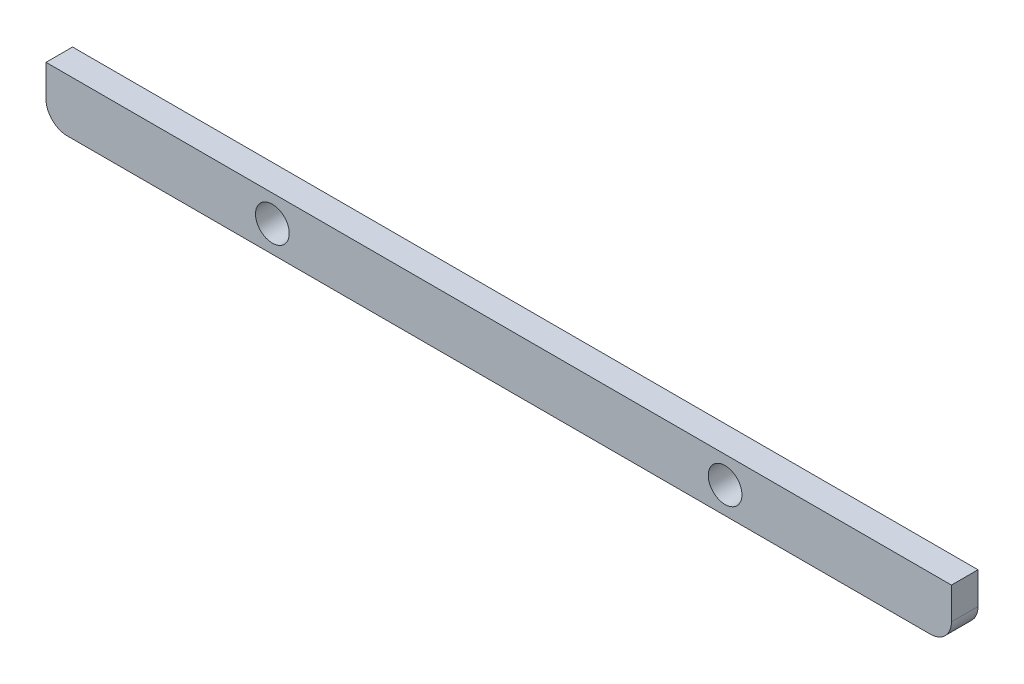
SolidWorks part; units mm, degrees
ref_plane "Alzado" through (0, 0, 0) normal (0, 0, 1) x (1, 0, 0)
ref_plane "Planta" through (0, 0, 0) normal (0, 1, 0) x (1, 0, 0)
ref_plane "Vista lateral" through (0, 0, 0) normal (1, 0, 0) x (0, 0, -1)
sketch "Croquis1" plane through (0, 0, 0) normal (0, 0, 1) x (1, 0, 0)
  line L1 (-85.24, 5) -> (85.24, 5)
  line L2 (-85.24, 5) -> (-85.24, -1)
  line L3 (-81.24, -5) -> (81.24, -5)
  line L4 (85.24, 5) -> (85.24, -1)
  line L5 (-85.24, 5) -> (85.24, -5) construction
  line L6 (-85.24, -5) -> (85.24, 5) construction
  arc A0 (81.24, -5) -> (85.24, -1) centre (81.24, -1) ccw
  arc A1 (-85.24, -1) -> (-81.24, -5) centre (-81.24, -1) ccw
  point P0 (0, 0)
  dimension "D3" = 4
  dimension "D1" = 170.48
  dimension "D2" = 10
extrude "Saliente-Extruir1" add sketch "Croquis1" along normal mid plane 5
sketch "Croquis2" plane through (0, 0, 2.5) normal (0, 0, 1) x (1, 0, 0)
  line L0 (-42.62, 0) -> (-85.24, 0) construction
  line L3 (-85.24, 5) -> (-85.24, -1) construction
  line L4 (-42.62, 0) -> (0, 0) construction
  line L5 (0, 0) -> (42.62, 0) construction
  line L6 (42.62, 0) -> (85.24, 0) construction
  line L7 (85.24, -1) -> (85.24, 5) construction
  circle A0 centre (42.62, 0) radius 3.175
  circle A1 centre (-42.62, 0) radius 3.175
  point P4 (0, 0)
  dimension "D1" = 6.35
extrude "Cortar-Extruir1" cut sketch "Croquis2" against normal through all
